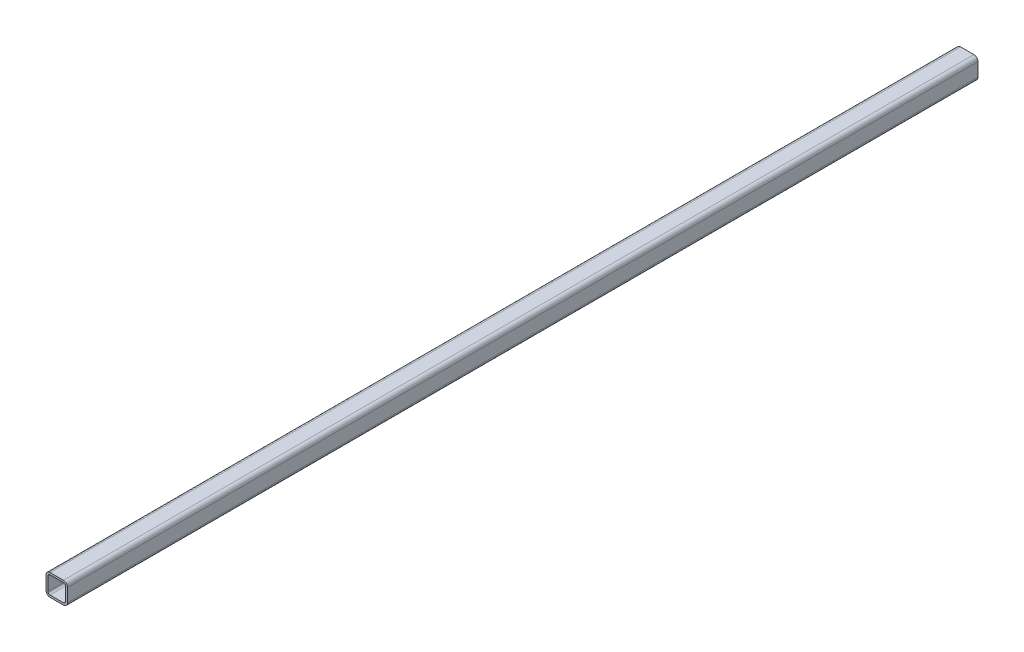
SolidWorks part; units mm, degrees
ref_plane "Płaszczyzna przednia" through (0, 0, 0) normal (0, 0, 1) x (1, 0, 0)
ref_plane "Płaszczyzna górna" through (0, 0, 0) normal (0, 1, 0) x (1, 0, 0)
ref_plane "Płaszczyzna prawa" through (0, 0, 0) normal (1, 0, 0) x (0, 0, -1)
sketch "Szkic1" plane through (0, 0, 0) normal (0, 0, 1) x (1, 0, 0)
  line L1 (9.53, 0) -> (41.27, 0)
  line L2 (0, 9.53) -> (0, 41.27)
  line L3 (9.53, 50.8) -> (41.27, 50.8)
  line L4 (50.8, 9.53) -> (50.8, 41.27)
  line L5 (9.52, 46.04) -> (41.28, 46.04)
  line L6 (4.76, 41.28) -> (4.76, 9.52)
  line L7 (9.52, 4.76) -> (41.28, 4.76)
  line L8 (46.04, 41.28) -> (46.04, 9.52)
  arc A0 (4.76, 9.52) -> (9.52, 4.76) centre (9.52, 9.52) ccw
  arc A1 (41.28, 4.76) -> (46.04, 9.52) centre (41.28, 9.52) ccw
  arc A2 (46.04, 41.28) -> (41.28, 46.04) centre (41.28, 41.28) ccw
  arc A3 (4.76, 41.28) -> (9.52, 46.04) centre (9.52, 41.28) cw
  arc A4 (41.27, 50.8) -> (50.8, 41.27) centre (41.27, 41.27) cw
  arc A5 (50.8, 9.53) -> (41.27, 0) centre (41.27, 9.53) cw
  arc A6 (9.53, 0) -> (0, 9.53) centre (9.53, 9.53) cw
  arc A7 (0, 41.27) -> (9.53, 50.8) centre (9.53, 41.27) cw
  dimension "D7" = 4.76
  dimension "D8" = 9.53
  dimension "D1" = 50.8
  dimension "D2" = 50.8
  dimension "D3" = 41.28
  dimension "D4" = 41.28
  dimension "D5" = 4.76
  dimension "D6" = 4.76
extrude "Dodanie-wyciągnięcie1" add sketch "Szkic1" along normal blind 2150.8
